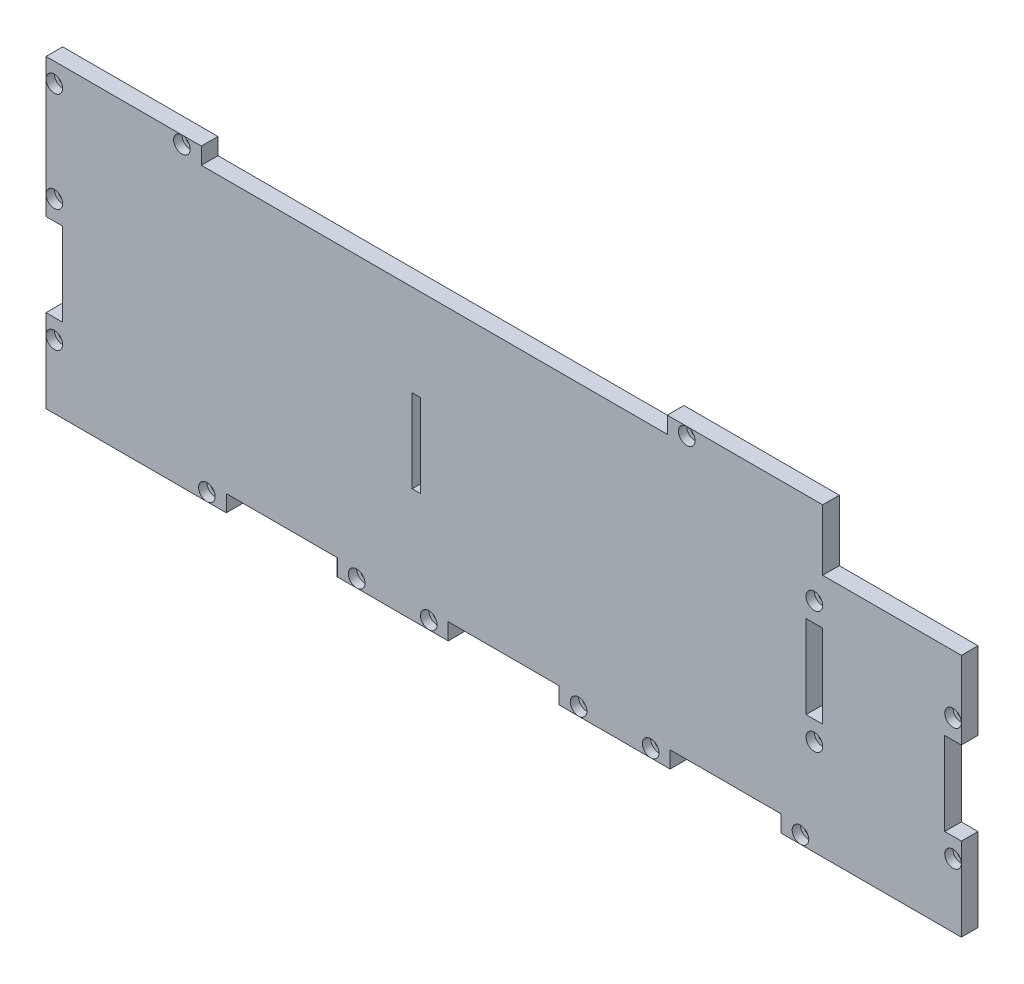
SolidWorks part; units mm, degrees
ref_plane "Plan de face" through (0, 0, 0) normal (0, 0, 1) x (1, 0, 0)
ref_plane "Plan de dessus" through (0, 0, 0) normal (0, 1, 0) x (1, 0, 0)
ref_plane "Plan de droite" through (0, 0, 0) normal (1, 0, 0) x (0, 0, -1)
sketch "Esquisse2" plane through (0, 0, 0) normal (0, 0, 1) x (1, 0, 0)
  line L1 (0, 0) -> (330, 0)
  line L2 (0, 0) -> (0, 110)
  line L3 (0, 110) -> (330, 110)
  line L4 (330, 0) -> (330, 110)
  dimension "D1" = 110
  dimension "D2" = 330
extrude "Boss.-Extru.1" add sketch "Esquisse2" along normal blind 6
sketch "Esquisse4" plane through (0, 0, 6) normal (0, 0, 1) x (1, 0, 0)
  line L0 (56, 104) -> (224, 104)
  line L1 (0, 110) -> (0, 0) construction
  line L2 (0, 60) -> (6, 60)
  line L3 (0, 60) -> (0, 30)
  line L4 (0, 30) -> (6, 30)
  line L5 (6, 60) -> (6, 30)
  line L6 (330, 110) -> (280, 110)
  line L7 (330, 110) -> (330, 88)
  line L8 (330, 88) -> (280, 88)
  line L9 (0, 0) -> (330, 0) construction
  line L10 (65, 0) -> (105, 0)
  line L11 (65, 0) -> (65, 6)
  line L12 (65, 6) -> (105, 6)
  line L13 (105, 0) -> (105, 6)
  line L14 (330, 0) -> (330, 110) construction
  line L15 (145, 0) -> (185, 0)
  line L16 (145, 0) -> (145, 6)
  line L17 (145, 6) -> (185, 6)
  line L18 (185, 0) -> (185, 6)
  line L19 (225, 0) -> (265, 0)
  line L20 (225, 0) -> (225, 6)
  line L21 (225, 6) -> (265, 6)
  line L22 (265, 0) -> (265, 6)
  line L23 (280, 110) -> (280, 88)
  line L24 (330, 30) -> (324, 30)
  line L25 (330, 30) -> (330, 60)
  line L26 (330, 60) -> (324, 60)
  line L27 (330, 110) -> (0, 110) construction
  line L28 (56, 110) -> (224, 110)
  line L29 (224, 110) -> (224, 104)
  line L31 (132, 71) -> (135, 71)
  line L32 (324, 30) -> (324, 60)
  line L33 (132, 71) -> (132, 41)
  line L34 (132, 41) -> (135, 41)
  line L35 (135, 71) -> (135, 41)
  line L36 (56, 110) -> (56, 104)
  line L37 (280, 71.5) -> (274, 71.5)
  line L38 (280, 71.5) -> (280, 41.5)
  line L39 (280, 41.5) -> (274, 41.5)
  line L40 (274, 71.5) -> (274, 41.5)
  dimension "D1" = 30
  dimension "D2" = 30
  dimension "D3" = 6
  dimension "D4" = 168
  dimension "D5" = 6
  dimension "D6" = 56
  dimension "D7" = 3
  dimension "D8" = 30
  dimension "D9" = 6
  dimension "D10" = 22
  dimension "D11" = 50
  dimension "D12" = 30
  dimension "D13" = 6
  dimension "D14" = 40
  dimension "D15" = 65
  dimension "D16" = 40
  dimension "D17" = 40
  dimension "D18" = 6
  dimension "D19" = 40
  dimension "D20" = 40
  dimension "D21" = 6
  dimension "D22" = 30
  dimension "D23" = 6
  dimension "D24" = 30
  dimension "D25" = 38.5
  dimension "D26" = 50
  dimension "D27" = 6
  dimension "D28" = 132
  dimension "D29" = 41
extrude "Enlèv. mat.-Extru.1" cut sketch "Esquisse4" against normal through all
sketch "Esquisse5" plane through (0, 0, 6) normal (0, 0, 1) x (1, 0, 0)
  line L0 (56, 110) -> (0, 110) construction
  line L1 (0, 110) -> (0, 60) construction
  line L2 (56, 110) -> (56, 104) construction
  line L3 (6, 60) -> (0, 60) construction
  line L4 (0, 30) -> (6, 30) construction
  line L5 (0, 30) -> (0, 0) construction
  line L6 (65, 6) -> (65, 0) construction
  line L7 (0, 0) -> (65, 0) construction
  line L8 (105, 0) -> (145, 0) construction
  line L9 (105, 0) -> (105, 6) construction
  line L10 (145, 6) -> (145, 0) construction
  line L11 (185, 0) -> (225, 0) construction
  line L12 (185, 0) -> (185, 6) construction
  line L13 (225, 6) -> (225, 0) construction
  line L14 (265, 0) -> (265, 6) construction
  line L15 (265, 0) -> (330, 0) construction
  line L16 (324, 30) -> (330, 30) construction
  line L17 (330, 0) -> (330, 30) construction
  line L18 (330, 60) -> (330, 88) construction
  line L19 (330, 60) -> (324, 60) construction
  line L20 (280, 41.5) -> (280, 71.5) construction
  line L21 (280, 71.5) -> (274, 71.5) construction
  line L22 (274, 41.5) -> (280, 41.5) construction
  line L23 (280, 110) -> (224, 110) construction
  line L24 (224, 104) -> (224, 110) construction
  circle A0 centre (3, 23) radius 1.5
  circle A1 centre (58, 3) radius 1.5
  circle A2 centre (112, 3) radius 1.5
  circle A3 centre (138, 3) radius 1.5
  circle A4 centre (192, 3) radius 1.5
  circle A5 centre (218, 3) radius 1.5
  circle A6 centre (272, 3) radius 1.5
  circle A7 centre (277, 34.5) radius 1.5
  circle A8 centre (277, 78.5) radius 1.5
  circle A9 centre (327, 67) radius 1.5
  circle A10 centre (327, 23) radius 1.5
  circle A11 centre (231, 107) radius 1.5
  circle A12 centre (49, 107) radius 1.5
  circle A13 centre (3, 103) radius 1.5
  circle A14 centre (3, 67) radius 1.5
  point P34 (56, 107)
  dimension "D1" = 3
  dimension "D2" = 3
  dimension "D3" = 7
  dimension "D4" = 3
  dimension "D5" = 3
  dimension "D6" = 7
  dimension "D7" = 3
  dimension "D8" = 7
  dimension "D9" = 3
  dimension "D10" = 3
  dimension "D11" = 7
  dimension "D12" = 3
  dimension "D13" = 3
  dimension "D14" = 7
  dimension "D15" = 3
  dimension "D16" = 3
  dimension "D17" = 3
  dimension "D18" = 7
  dimension "D19" = 3
  dimension "D20" = 3
  dimension "D21" = 7
  dimension "D22" = 3
  dimension "D23" = 3
  dimension "D24" = 3
  dimension "D25" = 3
  dimension "D26" = 7
  dimension "D27" = 7
  dimension "D28" = 3
  dimension "D29" = 7
  dimension "D30" = 3
  dimension "D31" = 3
  dimension "D32" = 7
  dimension "D33" = 3
  dimension "D34" = 3
  dimension "D35" = 3
  dimension "D37" = 3
  dimension "D38" = 3
  dimension "D39" = 7
  dimension "D40" = 3
  dimension "D41" = 3
  dimension "D42" = 7
  dimension "D43" = 3
  dimension "D44" = 3
  dimension "D45" = 7
  dimension "D36" = 7
extrude "Enlèv. mat.-Extru.2" cut sketch "Esquisse5" against normal blind 6
sketch "Esquisse6" plane through (0, 0, 6) normal (0, 0, 1) x (1, 0, 0)
  circle A0 centre (3, 67) radius 2.995
  circle A1 centre (3, 23) radius 2.995
  circle A2 centre (3, 103) radius 2.995
  circle A3 centre (49, 107) radius 2.995
  circle A4 centre (231, 107) radius 2.995
  circle A5 centre (277, 78.5) radius 3
  circle A6 centre (327, 67) radius 2.995
  circle A7 centre (277, 34.5) radius 2.995
  circle A8 centre (327, 23) radius 2.995
  circle A9 centre (272, 3) radius 2.995
  circle A10 centre (218, 3) radius 2.995
  circle A11 centre (192, 3) radius 2.995
  circle A12 centre (138, 3) radius 2.995
  circle A13 centre (112, 3) radius 2.995
  circle A14 centre (58, 3) radius 2.995
  dimension "D1" = 5.99
  dimension "D2" = 5.99
  dimension "D3" = 5.99
  dimension "D4" = 5.99
  dimension "D5" = 5.99
  dimension "D6" = 5.99
  dimension "D7" = 5.99
  dimension "D8" = 5.99
  dimension "D9" = 5.99
  dimension "D10" = 5.99
  dimension "D11" = 5.99
  dimension "D12" = 5.99
  dimension "D13" = 6
  dimension "D14" = 5.99
  dimension "D15" = 5.99
extrude "Enlèv. mat.-Extru.3" cut sketch "Esquisse6" against normal blind 3
